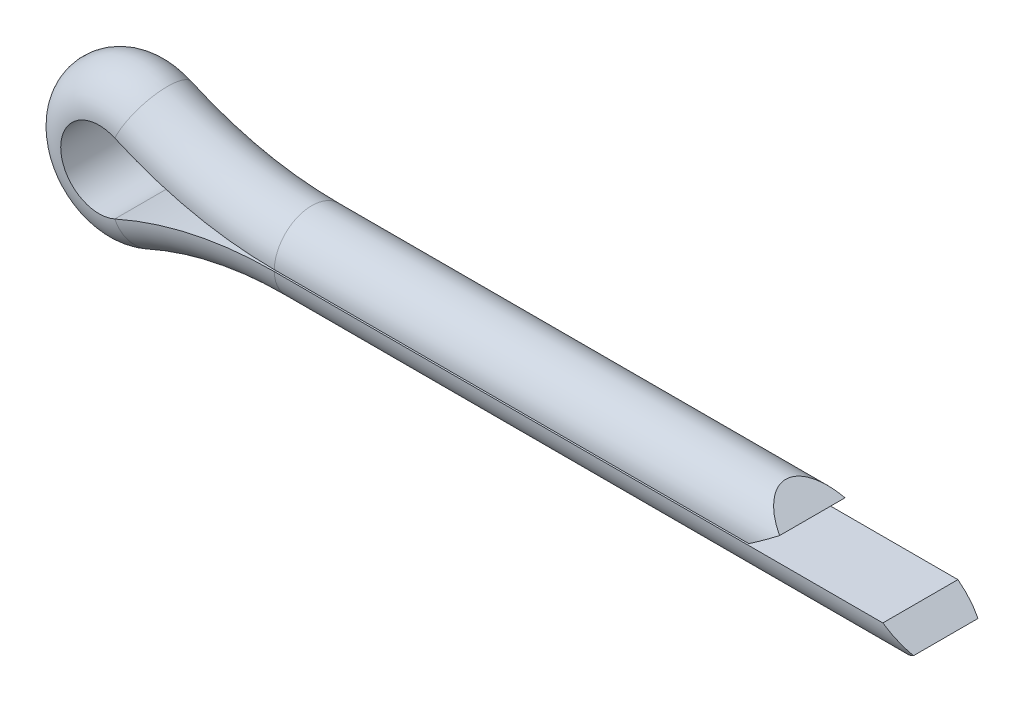
SolidWorks part; units mm, degrees
ref_plane "前视基准面" through (0, 0, 0) normal (0, 0, 1) x (1, 0, 0)
ref_plane "上视基准面" through (0, 0, 0) normal (0, 1, 0) x (1, 0, 0)
ref_plane "右视基准面" through (0, 0, 0) normal (1, 0, 0) x (0, 0, -1)
sketch "尺寸草图" plane through (0, 0, 0) normal (0, 0, 1) x (1, 0, 0)
  line L0 (8.1, 0.45) -> (2.1, 0.45)
  line L1 (2.1, -0.45) -> (9.7, -0.45)
  line L2 (2.1, 0) -> (27.3859, 0) construction
  line L3 (2.1, 0) -> (2.1, -0.0723) construction
  line L4 (-0.9, 0) -> (-0.9, 18.8979) construction
  arc A0 (2.1, 0.45) -> (0.3688, 0.821) centre (2.1, 4.675) cw
  arc A1 (0.3688, 0.821) -> (0.3688, -0.821) centre (0, 0) ccw
  arc A2 (0.3688, -0.821) -> (2.1, -0.45) centre (2.1, -4.675) cw
  dimension "c" = 1.8
  dimension "d1" = 0.9
  dimension "b" = 3
  dimension "l" = 6
  dimension "a" = 1.6
ref_plane "基准面1" through (8.1, 0.45, 0) normal (-1, 0, 0) x (0, 0, 1)
sketch "草图2" plane through (8.1, 0.45, 0) normal (-1, 0, 0) x (0, 0, 1)
  line L0 (0, -1.35) -> (0, 0.45) construction
  line L1 (-0.4499, -0.44) -> (0.4499, -0.44)
  arc A0 (0.4499, -0.44) -> (-0.4499, -0.44) centre (0, -0.45) ccw
  dimension "d" = 0.9
  dimension "D1" = 0.01
sweep "扫描2" add profiles "草图2" path "尺寸草图"
sketch "草图3" plane through (0, 0, 0) normal (0, 0, 1) x (1, 0, 0)
  line L0 (2.1, 0) -> (2.1, 16.2682) construction
  line L1 (2.1, 0) -> (37.4999, 0) construction
  line L2 (9.7, -0.45) -> (9.7, -0.01) construction
  line L3 (8.1, 0.22) -> (7.7822, 0.45)
  line L4 (8.1, 0.45) -> (2.1, 0.45) construction
  line L5 (2.1, -0.45) -> (9.7, -0.45) construction
  line L6 (8.1, 0.22) -> (7.7752, 0)
  line L7 (9.7, -0.23) -> (9.3822, 0)
  line L9 (9.7, -0.23) -> (9.3752, -0.45)
  line L10 (9.3822, 0) -> (7.7752, 0)
  line L11 (7.7822, 0.45) -> (9.71, 0.45)
  line L12 (9.71, 0.45) -> (9.71, -0.45)
  line L13 (9.71, -0.45) -> (9.3752, -0.45)
  line L14 (8.1, 0.45) -> (8.1, 0.01) construction
  dimension "D1" = 0.01
  dimension "D3" = 70
  dimension "D4" = 70
extrude "切除-拉伸1" cut sketch "草图3" against normal through all and the other way through all
